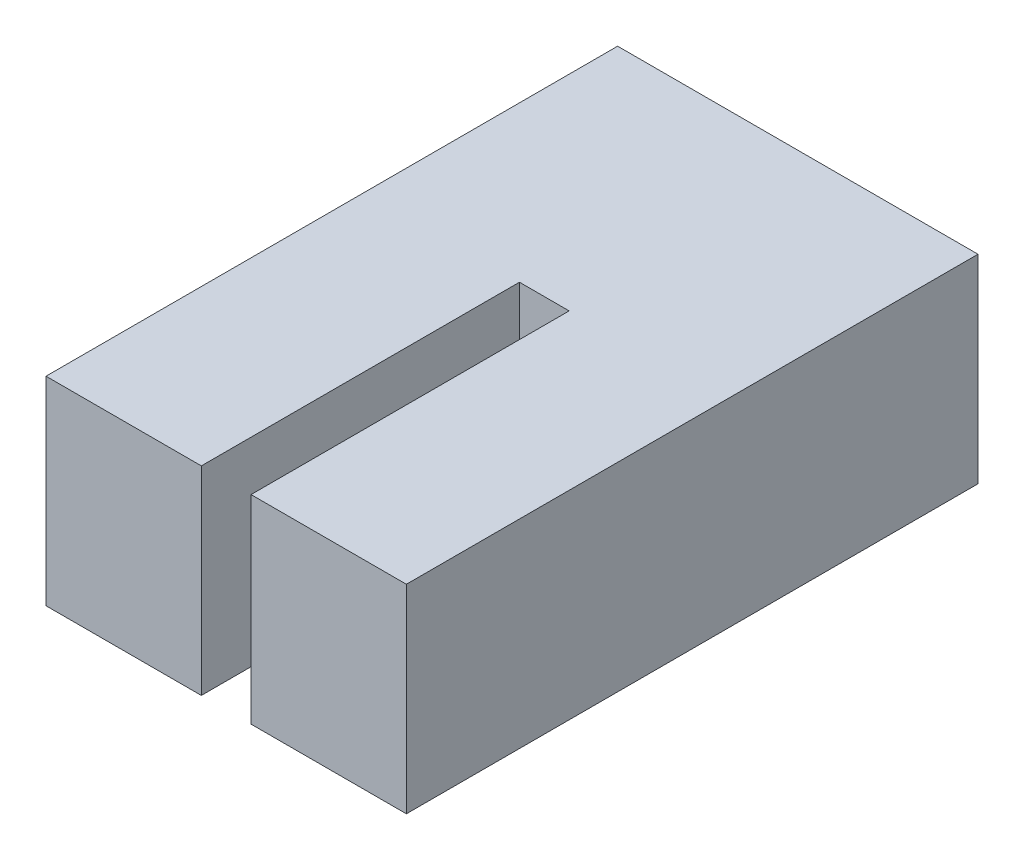
SolidWorks part; units mm, degrees
ref_plane "Plan de face" through (0, 0, 0) normal (0, 0, 1) x (1, 0, 0)
ref_plane "Plan de dessus" through (0, 0, 0) normal (0, 1, 0) x (1, 0, 0)
ref_plane "Plan de droite" through (0, 0, 0) normal (1, 0, 0) x (0, 0, -1)
sketch "Sketch1" plane through (0, 0, 0) normal (0, 0, 1) x (1, 0, 0)
  line L0 (0, 0) -> (0, 8)
  line L1 (0, 8) -> (14.5, 8)
  line L2 (14.5, 8) -> (14.5, 0)
  line L3 (14.5, 0) -> (0, 0)
  dimension "D1" = 14.5
  dimension "D2" = 8
extrude "Boss-Extrude1" add sketch "Sketch1" along normal blind 23
sketch "Sketch2" plane through (0, 0, 0) normal (0, -1, 0) x (1, 0, 0)
  line L0 (6.25, 23) -> (6.25, 10.2)
  line L1 (0, 23) -> (14.5, 23) construction
  line L2 (6.25, 10.2) -> (8.25, 10.2)
  line L3 (8.25, 10.2) -> (8.25, 23)
  line L4 (8.25, 23) -> (6.25, 23)
  line L5 (8.25, 23) -> (6.25, 23)
extrude "Cut-Extrude1" cut sketch "Sketch2" along normal through all and the other way through all contours L0 L2 L3
